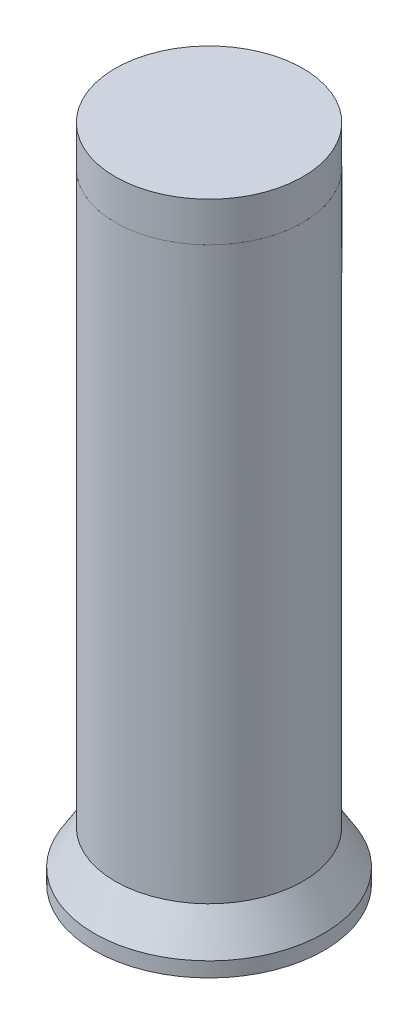
SolidWorks part; units mm, degrees
ref_plane "前基準面" through (0, 0, 0) normal (0, 0, 1) x (1, 0, 0)
ref_plane "上基準面" through (0, 0, 0) normal (0, 1, 0) x (1, 0, 0)
ref_plane "右基準面" through (0, 0, 0) normal (1, 0, 0) x (0, 0, -1)
sketch "草圖1" plane through (0, 0, 0) normal (0, 0, 1) x (1, 0, 0)
  line L0 (0, 0) -> (0, 6)
  line L1 (8.5, 20) -> (8.5, 268)
  line L2 (8.5, 268) -> (46.5, 268)
  line L3 (46.5, 292.2142) -> (46.5, -36.2143) construction
  line L4 (0, 0) -> (46.5, 0)
  line L5 (0, 6) -> (8.5, 20)
  line L6 (46.5, 268) -> (46.5, 0)
  dimension "D1" = 93
  dimension "D2" = 76
  dimension "D3" = 268
  dimension "D4" = 6
  dimension "D5" = 20
revolve "旋轉1" add sketch "草圖1" angle 360 about L3
sketch "草圖2" plane through (0, 268, 0) normal (0, 1, 0) x (1, 0, 0)
  circle A0 centre (46.5, 0) radius 31.5
  circle A1 centre (46.5, 0) radius 46.5 construction
  dimension "D1" = 63
extrude "除料-伸長1" cut sketch "草圖2" against normal through all
sketch "草圖3" plane through (0, 0, 0) normal (0, -1, 0) x (1, 0, 0)
  circle A0 centre (46.5, 0) radius 34
  circle A1 centre (46.5, 0) radius 31.5 construction
  dimension "D1" = 68
extrude "除料-伸長2" cut sketch "草圖3" against normal blind 9
sketch "草圖4" plane through (0, 0, 0) normal (0, 0, 1) x (1, 0, 0)
  line L0 (0, 275.1111) -> (0, 251)
  line L1 (0, 251) -> (90.8803, 251)
  line L2 (90.8803, 251) -> (90.8803, 275.1111)
  line L3 (90.8803, 275.1111) -> (0, 275.1111)
  dimension "D1" = 251
extrude "除料-伸長3" cut sketch "草圖4" against normal mid plane 100
sketch "草圖5" plane through (0, 251, 0) normal (0, 1, 0) x (1, 0, 0)
  circle A0 centre (46.5, 0) radius 38
  circle A1 centre (46.5, 0) radius 38 construction
  dimension "D1" = 76
extrude "填料-伸長1" add sketch "草圖5" along normal blind 16 separate body
